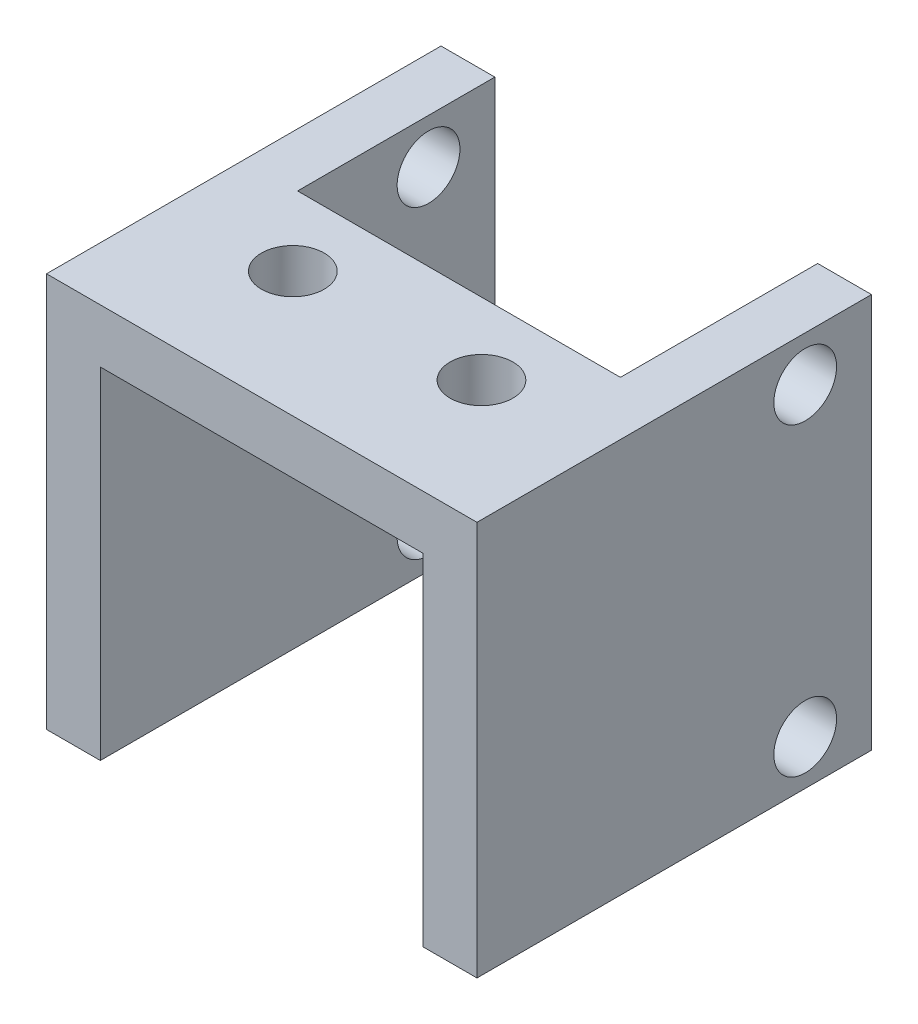
SolidWorks part; units mm, degrees
ref_plane "정면" through (0, 0, 0) normal (0, 0, 1) x (1, 0, 0)
ref_plane "윗면" through (0, 0, 0) normal (0, 1, 0) x (1, 0, 0)
ref_plane "우측면" through (0, 0, 0) normal (1, 0, 0) x (0, 0, -1)
ref_plane "평면4" through (-11.9973, 0, 0) normal (-1, 0, 0) x (0, -1, 0)
sketch "스케치1" plane through (-11.9973, 0, 0) normal (-1, 0, 0) x (0, -1, 0)
  line L0 (0, -26.3009) -> (22, -26.3009)
  line L1 (22, -26.3009) -> (22, -4.3088)
  line L2 (22, -4.3088) -> (0, -4.3088)
  line L3 (0, -4.3088) -> (0, -26.3009)
extrude "보스-돌출1" add sketch "스케치1" against normal blind 3
ref_plane "평면5" through (0, 0, -4.3088) normal (0, 0, 1) x (1, 0, 0)
sketch "스케치2" plane through (0, 0, -4.3088) normal (0, 0, 1) x (1, 0, 0)
  line L0 (12, 0) -> (-8.9973, 0)
  line L1 (-8.9973, 0) -> (-8.9973, -3)
  line L2 (-8.9973, -3) -> (9, -3)
  line L3 (9, -3) -> (9, -22)
  line L4 (9, -22) -> (12, -22)
  line L5 (12, -22) -> (12, 0)
extrude "보스-돌출2" add sketch "스케치2" against normal blind 10.9961
sketch "스케치3" plane through (0, 0, -15.3048) normal (0, 0, -1) x (-1, 0, 0)
  line L0 (-12, 0) -> (-9, 0)
  line L1 (-9, 0) -> (-9, -22)
  line L2 (-9, -22) -> (-12, -22)
  line L3 (-12, -22) -> (-12, 0)
extrude "보스-돌출3" add sketch "스케치3" along normal blind 10.9961
hole_wizard "Ø3.5 (3.5) 지름 구멍1" positions "스케치5" profile "스케치4" hole size "Ø3.5" standard "Ansi Metric"
sketch "스케치5" plane through (0, 0, 0) normal (0, 1, 0) x (1, 0, 0)
  point P0 (-5.2587, 11.3009)
  point P1 (5.2587, 11.3009)
sketch "스케치4" plane through (-5.2587, 0, -11.3009) normal (1, 0, 0) x (0, 0, 1)
  line L0 (0, 0) -> (0, 22)
  line L1 (0, 22) -> (1.75, 22)
  line L2 (1.75, 22) -> (1.75, 0)
  line L5 (1.75, 0) -> (0, 0)
  line L11 (0, -6.35) -> (0, 107.95) construction
  dimension "관통 구멍 지름" = 3.5
  dimension "관통 구멍 깊이" = 22
hole_wizard "Ø3.5 (3.5) 지름 구멍2" positions "스케치7" profile "스케치6" hole size "Ø3.5" standard "Ansi Metric"
sketch "스케치7" plane through (9, 0, 0) normal (-1, 0, 0) x (0, 0, 1)
  point P0 (-22.6063, -19.5)
  point P1 (-22.6063, -2.5)
sketch "스케치6" plane through (9, -19.5, -22.6063) normal (0, 1, 0) x (0, 0, 1)
  line L0 (0, 0) -> (0, 3)
  line L1 (0, 3) -> (1.75, 3)
  line L2 (1.75, 3) -> (1.75, 0)
  line L5 (1.75, 0) -> (0, 0)
  line L11 (0, -6.35) -> (0, 107.95) construction
  dimension "관통 구멍 지름" = 3.5
  dimension "관통 구멍 깊이" = 3
hole_wizard "Ø3.5 (3.5) 지름 구멍3" positions "스케치9" profile "스케치8" hole size "Ø3.5" standard "Ansi Metric"
sketch "스케치9" plane through (-8.9973, 0, 0) normal (1, 0, 0) x (0, 0, -1)
  point P0 (22.6063, -19.5)
  point P1 (22.6063, -2.5)
sketch "스케치8" plane through (-8.9973, -19.5, -22.6063) normal (0, 1, 0) x (0, 0, -1)
  line L0 (0, 0) -> (0, 3)
  line L1 (0, 3) -> (1.75, 3)
  line L2 (1.75, 3) -> (1.75, 0)
  line L5 (1.75, 0) -> (0, 0)
  line L11 (0, -6.35) -> (0, 107.95) construction
  dimension "관통 구멍 지름" = 3.5
  dimension "관통 구멍 깊이" = 3
